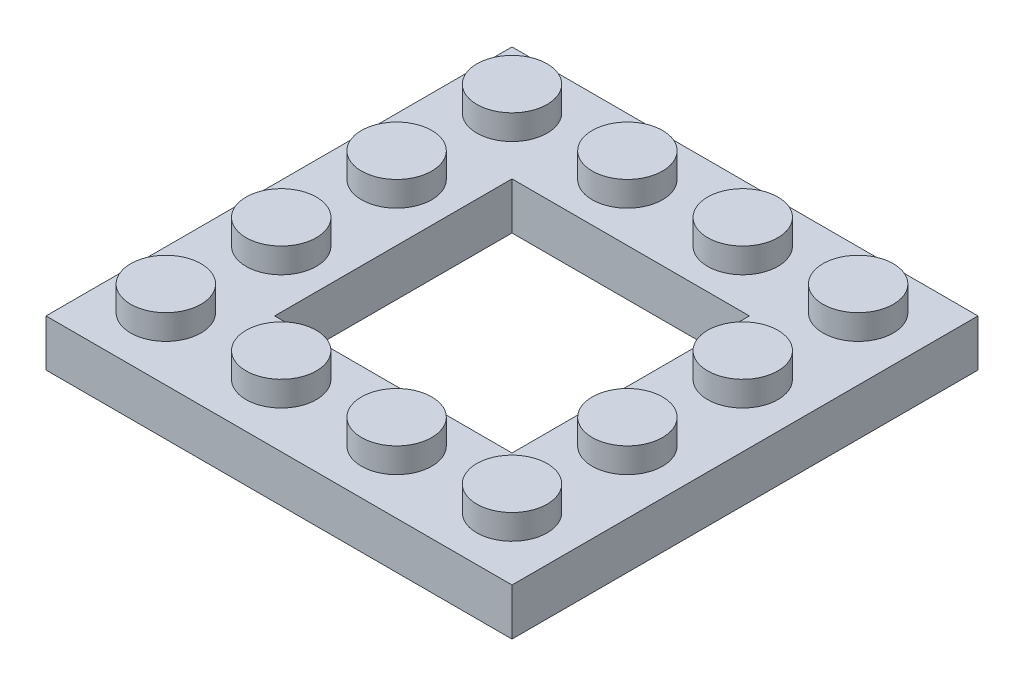
SolidWorks part; units mm, degrees
ref_plane "Спереди" through (0, 0, 0) normal (0, 0, 1) x (1, 0, 0)
ref_plane "Сверху" through (0, 0, 0) normal (0, 1, 0) x (1, 0, 0)
ref_plane "Справа" through (0, 0, 0) normal (1, 0, 0) x (0, 0, -1)
sketch "Эскиз1" plane through (0, 0, 0) normal (0, 1, 0) x (1, 0, 0)
  line L1 (15.9, -15.9) -> (-15.9, -15.9)
  line L2 (15.9, -15.9) -> (15.9, 15.9)
  line L3 (15.9, 15.9) -> (-15.9, 15.9)
  line L4 (-15.9, -15.9) -> (-15.9, 15.9)
  line L5 (15.9, -15.9) -> (-15.9, 15.9) construction
  line L6 (15.9, 15.9) -> (-15.9, -15.9) construction
  point P0 (0, 0)
  dimension "D1" = 31.8
  dimension "D2" = 31.8
extrude "Бобышка-Вытянуть1" add sketch "Эскиз1" along normal blind 3.2
sketch "Эскиз2" plane through (0, 3.2, 0) normal (0, 1, 0) x (1, 0, 0)
  line L0 (15.9, 15.9) -> (-15.9, 15.9) construction
  line L1 (-15.9, 15.9) -> (-15.9, -15.9) construction
  line L2 (-15.9, -15.9) -> (15.9, -15.9) construction
  line L3 (8.1, 8.1) -> (-8.1, 8.1)
  line L4 (8.1, 8.1) -> (8.1, -8.1)
  line L5 (8.1, -8.1) -> (-8.1, -8.1)
  line L6 (-8.1, 8.1) -> (-8.1, -8.1)
  line L7 (8.1, 8.1) -> (-8.1, -8.1) construction
  line L8 (8.1, -8.1) -> (-8.1, 8.1) construction
  circle A0 centre (-12, 12) radius 2.4
  circle A1 centre (-4.126, 12) radius 2.4
  circle A2 centre (3.748, 12) radius 2.4
  circle A3 centre (11.622, 12) radius 2.4
  circle A4 centre (-4.126, 4.126) radius 2.4
  circle A5 centre (3.748, 4.126) radius 2.4
  circle A6 centre (11.622, 4.126) radius 2.4
  circle A7 centre (-4.126, -3.748) radius 2.4
  circle A8 centre (3.748, -3.748) radius 2.4
  circle A9 centre (11.622, -3.748) radius 2.4
  circle A10 centre (-4.126, -11.622) radius 2.4
  circle A11 centre (3.748, -11.622) radius 2.4
  circle A12 centre (11.622, -11.622) radius 2.4
  circle A13 centre (-12, 4.126) radius 2.4
  circle A14 centre (-12, -3.748) radius 2.4
  circle A15 centre (-12, -11.622) radius 2.4
  point P6 (0, 0)
  dimension "D1" = 3.9
  dimension "D2" = 3.9
  dimension "D5" = 7.8
  dimension "D6" = 7.8
  dimension "D3" = 4
  dimension "D4" = 4
extrude "Вырез-Вытянуть3" cut sketch "Эскиз2" against normal through all contours L6 L5 L4 L3
sketch "Эскиз3" plane through (0, 3.2, 0) normal (0, 1, 0) x (1, 0, 0)
  line L0 (-15.9, 15.9) -> (-15.9, -15.9) construction
  line L2 (15.9, 15.9) -> (-15.9, 15.9) construction
  circle A0 centre (-12, 12) radius 2.4
  circle A1 centre (-4.126, 12) radius 2.4
  circle A2 centre (3.748, 12) radius 2.4
  circle A3 centre (11.622, 12) radius 2.4
  circle A4 centre (-12, 4.126) radius 2.4
  circle A5 centre (-12, -3.748) radius 2.4
  circle A6 centre (-12, -11.622) radius 2.4
  circle A7 centre (-4.126, -11.622) radius 2.4
  circle A8 centre (3.748, -11.622) radius 2.4
  circle A9 centre (11.622, -11.622) radius 2.4
  circle A10 centre (11.622, -3.748) radius 2.4
  circle A11 centre (11.622, 4.126) radius 2.4
  dimension "D1" = 3.9
  dimension "D2" = 3.9
  dimension "D3" = 4
  dimension "D4" = 4
  dimension "D5" = 4
  dimension "D6" = 3
extrude "Бобышка-Вытянуть2" add sketch "Эскиз3" along normal blind 1.7
sketch "Эскиз4" plane through (0, 0, 0) normal (0, -1, 0) x (1, 0, 0)
  line L0 (-15.9, -15.9) -> (-15.9, 15.9) construction
  line L1 (-15.9, 15.9) -> (15.9, 15.9) construction
  circle A0 centre (-12, 12) radius 2.5
  circle A1 centre (-4.126, 12) radius 2.5
  circle A2 centre (3.748, 12) radius 2.5
  circle A3 centre (11.622, 12) radius 2.5
  circle A4 centre (-12, 4.126) radius 2.5
  circle A5 centre (11.622, 4.126) radius 2.5
  circle A6 centre (-12, -3.748) radius 2.5
  circle A7 centre (11.622, -3.748) radius 2.5
  circle A8 centre (-12, -11.622) radius 2.5
  circle A9 centre (11.622, -11.622) radius 2.5
  circle A10 centre (-4.126, -11.622) radius 2.5
  circle A11 centre (3.748, -11.622) radius 2.5
  dimension "D1" = 3.9
  dimension "D2" = 3.9
  dimension "D3" = 4
  dimension "D4" = 4
  dimension "D5" = 3
extrude "Вырез-Вытянуть4" cut sketch "Эскиз4" against normal blind 1.8
